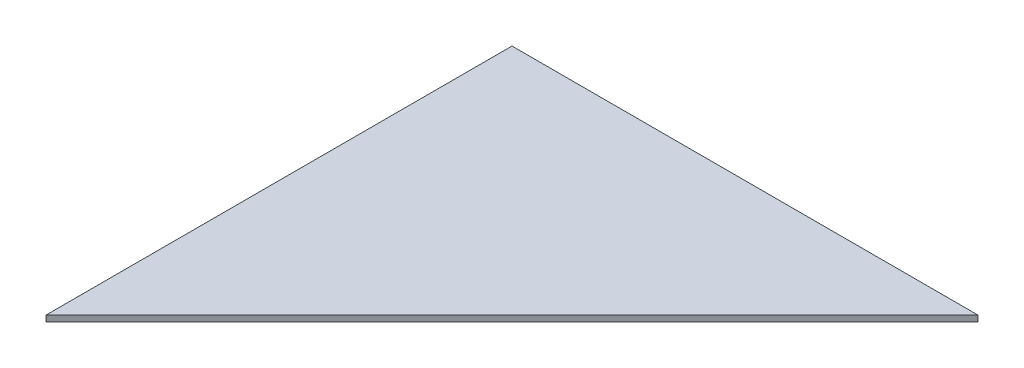
SolidWorks part; units mm, degrees
material "7075-O (SS)"
ref_plane "Front Plane" through (0, 0, 0) normal (0, 0, 1) x (1, 0, 0)
ref_plane "Top Plane" through (0, 0, 0) normal (0, 1, 0) x (1, 0, 0)
ref_plane "Right Plane" through (0, 0, 0) normal (1, 0, 0) x (0, 0, -1)
sketch "Sketch1" plane through (0, 0, 0) normal (0, 0, 1) x (1, 0, 0)
  line L0 (0, 0) -> (0, 8.5)
  line L1 (0, 8.5) -> (1, 8.5)
  line L2 (1, 8.5) -> (1, 13.5)
  line L3 (1, 13.5) -> (2, 13.5)
  line L4 (2, 13.5) -> (2, 2)
  line L5 (2, 2) -> (13.5, 2)
  line L6 (13.5, 2) -> (13.5, 1)
  line L7 (13.5, 1) -> (8.5, 1)
  line L8 (8.5, 1) -> (8.5, 0)
  line L9 (8.5, 0) -> (0, 0)
  line L10 (100, 0) -> (91.5, 0)
  line L11 (91.5, 0) -> (91.5, 1)
  line L12 (91.5, 1) -> (86.5, 1)
  line L13 (86.5, 1) -> (86.5, 2)
  line L14 (86.5, 2) -> (98, 2)
  line L15 (98, 2) -> (98, 13.5)
  line L16 (98, 13.5) -> (99, 13.5)
  line L17 (99, 13.5) -> (99, 8.5)
  line L18 (99, 8.5) -> (100, 8.5)
  line L19 (100, 8.5) -> (100, 0)
  dimension "D1" = 8.5
  dimension "D2" = 8.5
  dimension "D3" = 1
  dimension "D4" = 1
  dimension "D5" = 1
  dimension "D6" = 1
  dimension "D7" = 5
  dimension "D8" = 5
  dimension "D9" = 8.5
  dimension "D10" = 5
  dimension "D11" = 1
  dimension "D12" = 1
  dimension "D13" = 1
  dimension "D14" = 1
  dimension "D15" = 8.5
  dimension "D16" = 5
  dimension "D17" = 100
extrude "Boss-Extrude1" add sketch "Sketch1" along normal blind 327.5
sketch "Sketch2" plane through (0, 2, 0) normal (0, 1, 0) x (1, 0, 0)
  line L0 (86.5, 0) -> (13.5, -73)
  line L1 (13.5, -327.5) -> (13.5, 0) construction
  line L2 (13.5, -73) -> (13.5, -85.0208)
  line L3 (13.5, -85.0208) -> (86.5, -12.0208)
  line L4 (86.5, -327.5) -> (86.5, 0) construction
  line L5 (86.5, -12.0208) -> (86.5, 0)
  dimension "D1" = 8.5
  dimension "D2" = 45
extrude "Boss-Extrude2" add sketch "Sketch2" against normal blind 2
sketch "Sketch3" plane through (0, 1, 0) normal (0, -1, 0) x (1, 0, 0)
  line L0 (13.5, 85.0208) -> (8.5, 90.0208)
  line L1 (8.5, 327.5) -> (8.5, 0) construction
  line L2 (13.5, 73) -> (8.5, 78)
  line L3 (8.5, 78) -> (8.5, 90.0208)
  line L4 (13.5, 85.0208) -> (13.5, 73)
  line L5 (13.5, 85.0208) -> (86.5, 12.0208) construction
  line L6 (86.5, 0) -> (13.5, 73) construction
  line L7 (86.5, 12.0208) -> (91.5, 7.0208)
  line L8 (91.5, 327.5) -> (91.5, 0) construction
  line L9 (91.5, 7.0208) -> (91.5, 0)
  line L10 (91.5, 0) -> (86.5, 0)
  line L11 (86.5, 0) -> (86.5, 12.0208)
  line M5 (13.5, 73) -> (13.5, 85.0208)
  line M8 (8.5, 327.5) -> (8.5, 0)
  dimension "D1" = 180
  dimension "D2" = 180
  dimension "D3" = 180
extrude "Boss-Extrude4" add sketch "Sketch3" along normal blind 1 contours L2 L0 M5 M8 | L11 L10 L9 L7
sketch "Sketch4" plane through (0, 0, 0) normal (0, -1, 0) x (1, 0, 0)
  line L0 (0, 327.5) -> (0, 0) construction
  line L1 (100, 327.5) -> (0, 327.5)
  line L2 (100, 327.5) -> (100, 319)
  line L3 (100, 319) -> (0, 319)
  line L4 (0, 327.5) -> (0, 319)
  dimension "D1" = 8.5
extrude "Boss-Extrude5" add sketch "Sketch4" against normal blind 2
sketch "Sketch5" plane through (0, 2, 0) normal (0, 1, 0) x (1, 0, 0)
  line L0 (13.5, -65.9289) -> (79.4289, 0)
  line L1 (13.5, -73) -> (13.5, 0) construction
  line L2 (79.4289, 0) -> (86.5, 0)
  line L3 (86.5, 0) -> (13.5, -73)
  line L4 (13.5, -73) -> (13.5, -65.9289)
  dimension "D1" = 5
extrude "Boss-Extrude6" add sketch "Sketch5" against normal blind 1 separate body
sketch "Sketch7" plane through (0, 2, 0) normal (0, 1, 0) x (1, 0, 0)
  line L0 (98, -327.5) -> (98, 0) construction
  line L1 (2, -327.5) -> (98, -327.5)
  line L2 (2, -327.5) -> (2, -326.5)
  line L3 (2, -326.5) -> (98, -326.5)
  line L4 (98, -327.5) -> (98, -326.5)
  circle A0 centre (26.5, -326.5) radius 5
  circle A1 centre (73.5, -326.5) radius 5
  dimension "D2" = 10
  dimension "D3" = 10
  dimension "D1" = 1
  dimension "D4" = 25.5
  dimension "D5" = 25.5
extrude "Cut-Extrude2" cut sketch "Sketch7" against normal blind 1 contours L3 A1 | A0
mirror "Mirror1" about plane through (1, 13.5, 327.5) normal (0, -1, 0) of bodies 107 110
sketch "Sketch8" plane through (0, 0, 0) normal (0, 0, -1) x (-1, 0, 0)
  line L1 (-100, 0) -> (0, 0)
  line L2 (-100, 0) -> (-100, 13.5)
  line L3 (-100, 13.5) -> (0, 13.5)
  line L4 (0, 0) -> (0, 13.5)
  dimension "D1" = 13.5
extrude "Cut-Extrude3" cut sketch "Sketch8" against normal blind 400
sketch "Sketch9" plane through (0, 0, 0) normal (0, 0, -1) x (-1, 0, 0)
  line L1 (-1, 18.5) -> (-2, 18.5)
  line L2 (-1, 18.5) -> (-1, 13.5)
  line L3 (-1, 13.5) -> (-2, 13.5)
  line L4 (-2, 18.5) -> (-2, 13.5)
extrude "Cut-Extrude4" cut sketch "Sketch9" against normal blind 84.5
sketch "Sketch14" plane through (0, 27, 0) normal (0, 1, 0) x (1, 0, 0)
  line L0 (8.5, 0) -> (8.5, -78)
  line L1 (8.5, -78) -> (86.5, 0)
  line L2 (86.5, 0) -> (8.5, 0)
extrude "Boss-Extrude8" add sketch "Sketch14" along normal blind 1 separate body
sketch "Sketch15" plane through (0, 0, 0) normal (0, 0, -1) x (-1, 0, 0)
  line L1 (-100, 27) -> (10.2614, 27)
  line L2 (-100, 27) -> (-100, -9.2651)
  line L3 (-100, -9.2651) -> (10.2614, -9.2651)
  line L4 (10.2614, 27) -> (10.2614, -9.2651)
extrude "Cut-Extrude7" cut sketch "Sketch15" against normal blind 400
